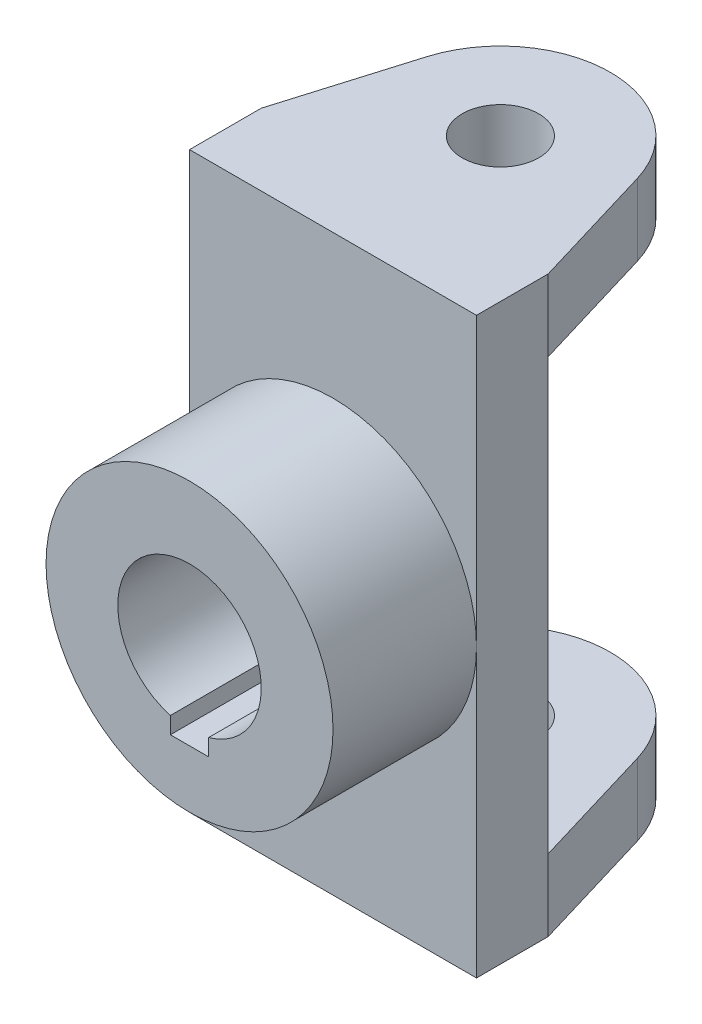
SolidWorks part; units mm, degrees
ref_plane "Front Plane" through (0, 0, 0) normal (0, 0, 1) x (1, 0, 0)
ref_plane "Top Plane" through (0, 0, 0) normal (0, 1, 0) x (1, 0, 0)
ref_plane "Right Plane" through (0, 0, 0) normal (1, 0, 0) x (0, 0, -1)
sketch "Sketch1" plane through (0, 0, 0) normal (0, 0, 1) x (1, 0, 0)
  line L0 (0, 0) -> (0, -40.0313) construction
  line L3 (-4, -14.4568) -> (-4, -17.9568)
  line L4 (-4, -17.9568) -> (4, -17.9568)
  line L5 (4, -14.4568) -> (4, -17.9568)
  circle A0 centre (0, 0) radius 30
  arc A1 (4, -14.4568) -> (-4, -14.4568) centre (0, 0) ccw
  dimension "D1" = 60
  dimension "D2" = 30
  dimension "D3" = 8
  dimension "D4" = 3.5
extrude "Boss-Extrude1" add sketch "Sketch1" against normal blind 30
sketch "Sketch2" plane through (0, 0, -30) normal (0, 0, -1) x (-1, 0, 0)
  line L1 (-30, 45) -> (30, 45)
  line L2 (-30, 45) -> (-30, -45)
  line L3 (-30, -45) -> (30, -45)
  line L4 (30, 45) -> (30, -45)
  line L5 (-30, 45) -> (30, -45) construction
  line L6 (-30, -45) -> (30, 45) construction
  point P0 (0, 0)
  dimension "D1" = 60
  dimension "D2" = 90
extrude "Boss-Extrude2" add sketch "Sketch2" along normal blind 15
sketch "Sketch3" plane through (0, 45, 0) normal (0, 1, 0) x (1, 0, 0)
  line L0 (-30, 30) -> (30, 30) construction
  line L1 (-30, 45) -> (-22.0329, 71.5993)
  line L2 (30, 45) -> (22.0329, 71.5993)
  line L3 (30, 45) -> (30, 30) construction
  line L4 (-30, 30) -> (30, 30) construction
  line L5 (-30, 45) -> (-30, 30) construction
  line L6 (30, 45) -> (30, 30)
  line L7 (-30, 30) -> (30, 30)
  line L8 (-30, 45) -> (-30, 30)
  arc A0 (22.0329, 71.5993) -> (-22.0329, 71.5993) centre (0, 65) ccw
  circle A1 centre (0, 65) radius 8
  dimension "D1" = 46
  dimension "D2" = 16
  dimension "D3" = 35
extrude "Boss-Extrude3" add sketch "Sketch3" along normal blind 15
mirror "Mirror1" about plane through (0, 0, 0) normal (0, 1, 0) of "Boss-Extrude3"
